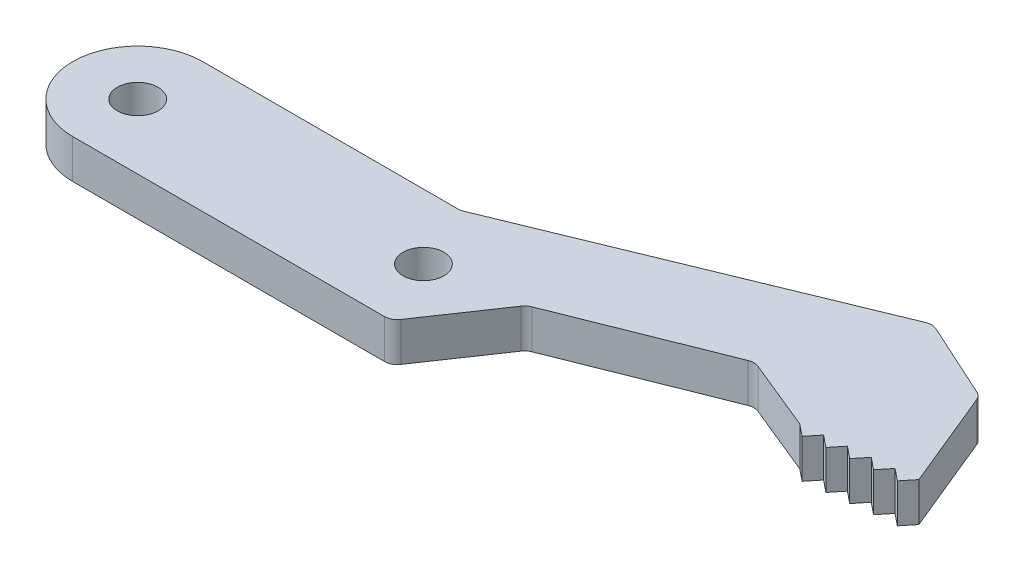
SolidWorks part; units mm, degrees
ref_plane "Front Plane" through (0, 0, 0) normal (0, 0, 1) x (1, 0, 0)
ref_plane "Top Plane" through (0, 0, 0) normal (0, 1, 0) x (1, 0, 0)
ref_plane "Right Plane" through (0, 0, 0) normal (1, 0, 0) x (0, 0, -1)
sketch "Sketch1" plane through (0, 0, 0) normal (0, 1, 0) x (1, 0, 0)
  line L1 (0, -5) -> (23.9989, -5)
  line L2 (0, 5) -> (19.6524, 5)
  line L3 (20.0327, 5.0751) -> (45.2294, 15.4347)
  line L4 (46.0242, 15.4199) -> (51.8314, 12.7746)
  line L5 (52.3417, 12.2448) -> (55.4426, 4.7029)
  line L6 (24.8266, -4.5611) -> (28.5649, 0.9541)
  line L7 (29.0223, 1.322) -> (40.9296, 6.07)
  line L8 (41.6788, 6.0666) -> (47.1446, 3.8294)
  line L11 (47.1446, 3.8294) -> (48.0617, 3.087)
  line L12 (48.0617, 3.087) -> (48.8042, 4.0041)
  line L13 (48.8042, 4.0041) -> (49.7213, 3.2617)
  line L14 (49.7213, 3.2617) -> (50.4638, 4.1788)
  line L15 (50.4638, 4.1788) -> (51.3809, 3.4364)
  line L16 (51.3809, 3.4364) -> (52.1234, 4.3535)
  line L17 (52.1234, 4.3535) -> (53.0405, 3.6111)
  line L18 (53.0405, 3.6111) -> (53.783, 4.5282)
  line L19 (53.783, 4.5282) -> (54.7001, 3.7858)
  line L20 (54.7001, 3.7858) -> (55.4426, 4.7029)
  circle A0 centre (0, 0) radius 1.575
  arc A1 (0, 5) -> (0, -5) centre (0, 0) ccw
  circle A2 centre (22, 0) radius 1.575
  arc A3 (28.5649, 0.9541) -> (29.0223, 1.322) centre (29.3927, 0.3931) cw
  arc A4 (40.9296, 6.07) -> (41.6788, 6.0666) centre (41.2999, 5.1412) cw
  arc A5 (51.8314, 12.7746) -> (52.3417, 12.2448) centre (51.4169, 11.8646) cw
  arc A6 (45.2294, 15.4347) -> (46.0242, 15.4199) centre (45.6096, 14.5098) cw
  arc A7 (19.6524, 5) -> (20.0327, 5.0751) centre (19.6524, 6) ccw
  arc A8 (23.9989, -5) -> (24.8266, -4.5611) centre (23.9989, -4) ccw
  point P27 (28.7372, 1.2083)
  point P30 (41.3048, 6.2197)
  point P33 (52.1913, 12.6106)
  point P36 (45.63, 15.5994)
  point P39 (19.85, 5)
  point P42 (24.5291, -5)
  dimension "D1" = 3.15
  dimension "D2" = 10
  dimension "D4" = 3.15
  dimension "D20" = 1
  dimension "D3" = 22
  dimension "D5" = 124.13
  dimension "D6" = 7.5
  dimension "D7" = 214.13
  dimension "D8" = 13.53
  dimension "D9" = 224
  dimension "D10" = 6.31
  dimension "D11" = 157.65
  dimension "D12" = 19.85
  dimension "D13" = 25.78
  dimension "D14" = 7.21
  dimension "D15" = 133.16
  dimension "D16" = 136.84
  dimension "D17" = 8.55
  dimension "D18" = 1.18
  dimension "D19" = 1.18
extrude "Boss-Extrude1" add sketch "Sketch1" along normal blind 3
scale "Ölçek1" scale about centroid uniform scaling yes scale factor 2
